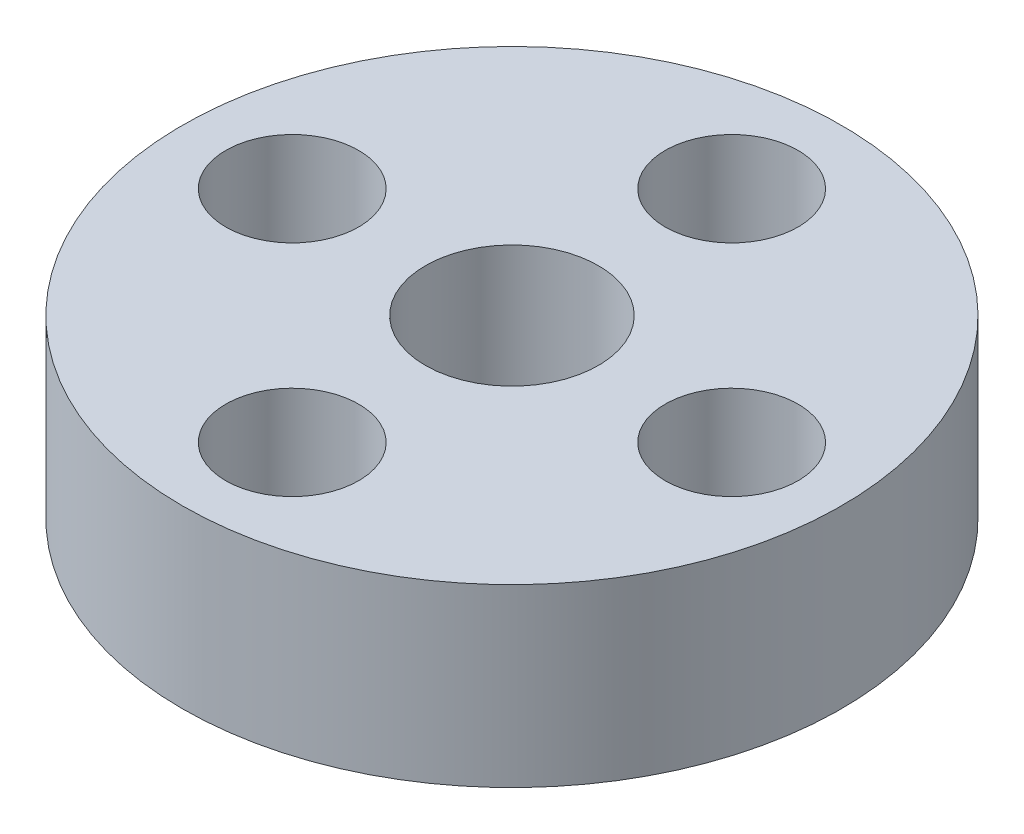
SolidWorks part; units mm, degrees
ref_plane "Front Plane" through (0, 0, 0) normal (0, 0, 1) x (1, 0, 0)
ref_plane "Top Plane" through (0, 0, 0) normal (0, 1, 0) x (1, 0, 0)
ref_plane "Right Plane" through (0, 0, 0) normal (1, 0, 0) x (0, 0, -1)
sketch "Sketch1" plane through (0, 0, 0) normal (0, 1, 0) x (1, 0, 0)
  circle A0 centre (0, 0) radius 9.525
  circle A1 centre (0, 6.35) radius 1.92
  circle A2 centre (6.35, 0) radius 1.92
  circle A3 centre (0, -6.35) radius 1.92
  circle A4 centre (-6.35, 0) radius 1.92
  circle A5 centre (0, 0) radius 2.5
  point P15 (0, 0)
  dimension "D1" = 19.05
  dimension "D2" = 3.84
  dimension "D3" = 6.35
  dimension "D4" = 4
  dimension "D6" = 5
extrude "Boss-Extrude1" add sketch "Sketch1" along normal blind 5.08
